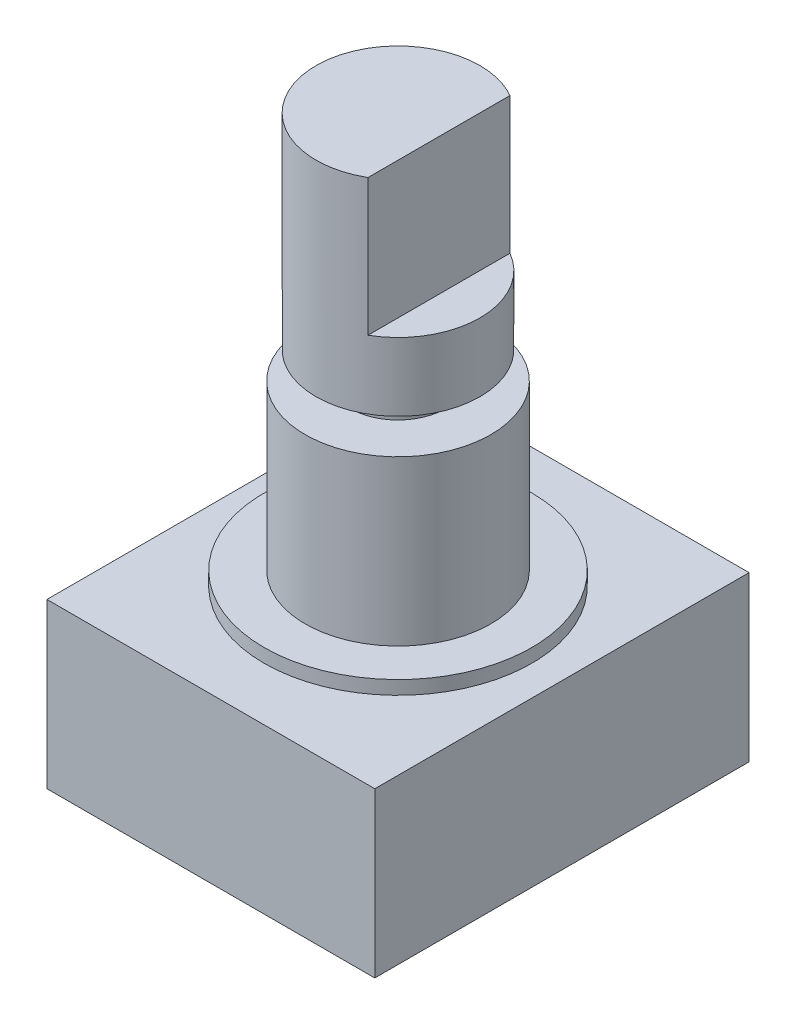
SolidWorks part; units mm, degrees
ref_plane "Front Plane" through (0, 0, 0) normal (0, 0, 1) x (1, 0, 0)
ref_plane "Top Plane" through (0, 0, 0) normal (0, 1, 0) x (1, 0, 0)
ref_plane "Right Plane" through (0, 0, 0) normal (1, 0, 0) x (0, 0, -1)
sketch "Sketch1" plane through (0, 0, 0) normal (0, 0, 1) x (1, 0, 0)
  line L0 (0, 15) -> (-3, 15)
  line L1 (-3, 15) -> (-3, 7.5)
  line L2 (-3, 7.5) -> (-1.75, 7.5)
  line L3 (-1.75, 7.5) -> (-1.75, 6.5)
  line L4 (-1.75, 6.5) -> (-3.4, 6.5)
  line L5 (-3.4, 6.5) -> (-3.4, 0.5)
  line L6 (-3.4, 0.5) -> (-4.9, 0.5)
  line L7 (-4.9, 0.5) -> (-4.9, 0)
  line L8 (0, 0) -> (0, 15) construction
  line L9 (-4.9, 0) -> (0, 0)
  line L10 (0, 15) -> (0, 0)
  point P4 (0, 0)
  point P11 (-3, 15)
  point P13 (0.1351, 15)
  point P14 (-1.6757, 5.3243)
  point P15 (-7.3533, 1.072)
  dimension "D1" = 15
  dimension "D2" = 7.5
  dimension "D3" = 6
  dimension "D4" = 1
  dimension "D5" = 3.5
  dimension "D6" = 6.8
  dimension "D7" = 0.5
  dimension "D8" = 9.8
revolve "Revolve1" add sketch "Sketch1" angle 360 about L8
sketch "Sketch2" plane through (0, 15, 0) normal (0, 1, 0) x (1, 0, 0)
  line L0 (-3, 0) -> (1.5, 0) construction
  line L1 (4.5, -2.5981) -> (1.5, -2.5981)
  line L2 (4.5, -2.5981) -> (4.5, 2.5981)
  line L3 (4.5, 2.5981) -> (1.5, 2.5981)
  line L4 (1.5, -2.5981) -> (1.5, 2.5981)
  line L5 (4.5, -2.5981) -> (1.5, 2.5981) construction
  line L6 (4.5, 2.5981) -> (1.5, -2.5981) construction
  circle A0 centre (0, 0) radius 3 construction
  point P0 (3, 0)
  point P9 (4.5, 2.5981)
  point P10 (1.5, -2.5981)
  dimension "D1" = 4.5
extrude "Cut-Extrude1" cut sketch "Sketch2" against normal blind 5
sketch "Sketch3" plane through (0, 0, 0) normal (0, -1, 0) x (-1, 0, 0)
  line L1 (6, 6.85) -> (-6, 6.85)
  line L2 (6, 6.85) -> (6, -6.85)
  line L3 (6, -6.85) -> (-6, -6.85)
  line L4 (-6, 6.85) -> (-6, -6.85)
  line L5 (6, 6.85) -> (-6, -6.85) construction
  line L6 (6, -6.85) -> (-6, 6.85) construction
  point P0 (0, 0)
  dimension "D1" = 12
  dimension "D2" = 13.7
extrude "Boss-Extrude1" add sketch "Sketch3" along normal blind 6
